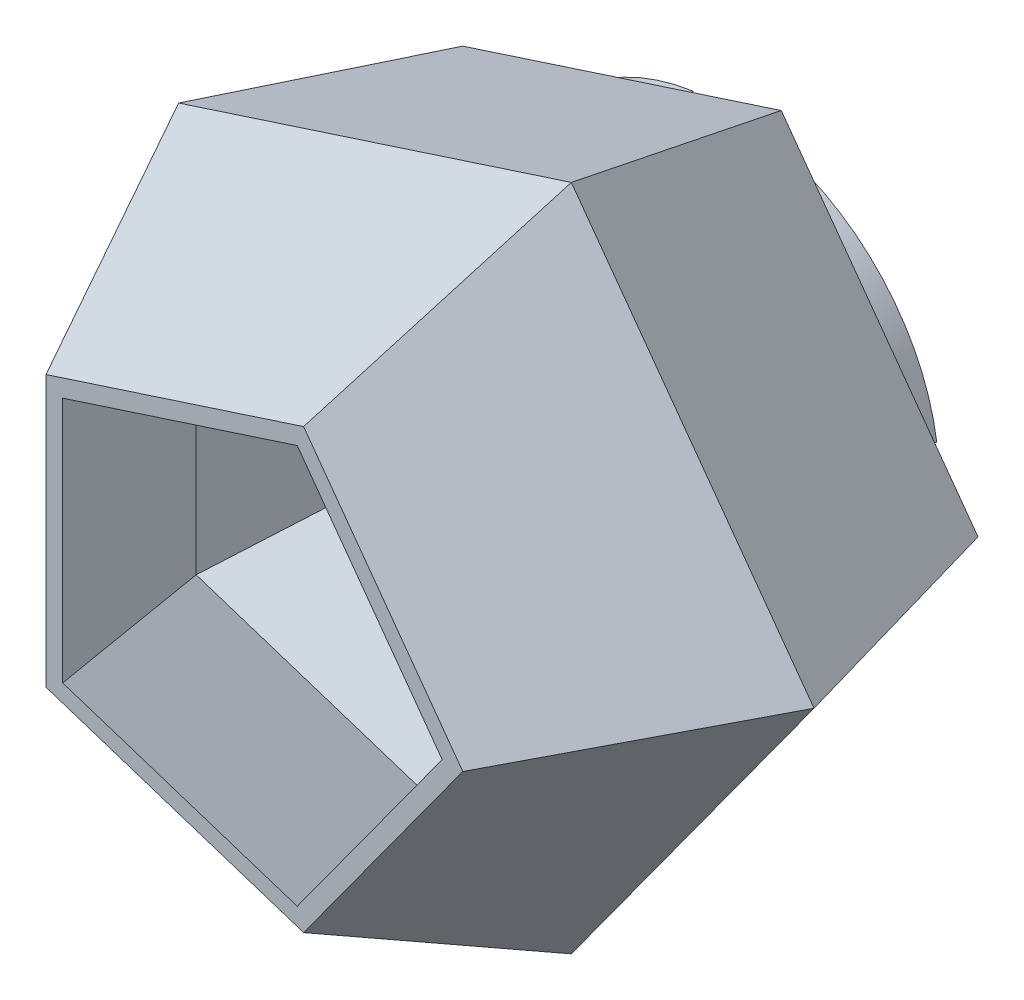
SolidWorks part; units mm, degrees
ref_plane "Alzado" through (0, 0, 0) normal (0, 0, 1) x (1, 0, 0)
ref_plane "Planta" through (0, 0, 0) normal (0, 1, 0) x (1, 0, 0)
ref_plane "Vista lateral" through (0, 0, 0) normal (1, 0, 0) x (0, 0, -1)
sketch "Croquis2" plane through (0, 0, 0) normal (0, 0, 1) x (1, 0, 0)
  line L1 (18.541, 0) -> (5.7295, 17.6336)
  line L2 (5.7295, 17.6336) -> (-15, 10.8981)
  line L3 (-15, 10.8981) -> (-15, -10.8981)
  line L4 (-15, -10.8981) -> (5.7295, -17.6336)
  line L5 (5.7295, -17.6336) -> (18.541, 0)
  circle A0 centre (0, 0) radius 15 construction
  dimension "D1" = 30
ref_plane "Plano1" through (0, 0, 15) normal (0, 0, 1) x (1, 0, 0)
sketch "Croquis3" plane through (0, 0, 15) normal (0, 0, 1) x (1, 0, 0)
  line L1 (22.8673, 0) -> (7.0664, 21.7481)
  line L2 (7.0664, 21.7481) -> (-18.5, 13.441)
  line L3 (-18.5, 13.441) -> (-18.5, -13.441)
  line L4 (-18.5, -13.441) -> (7.0664, -21.7481)
  line L5 (7.0664, -21.7481) -> (22.8673, 0)
  circle A0 centre (0, 0) radius 18.5 construction
  point P1 (7.1512, 21.7575)
  point P9 (22.7754, 0)
  point P10 (22.7754, 0)
  point P11 (22.8673, 0)
  dimension "D1" = 37
ref_plane "Plano2" through (0, 0, 30) normal (0, 0, 1) x (1, 0, 0)
sketch "Croquis4" plane through (0, 0, 30) normal (0, 0, 1) x (1, 0, 0)
  line L1 (15, 0) -> (4.6353, 14.2658)
  line L2 (4.6353, 14.2658) -> (-12.1353, 8.8168)
  line L3 (-12.1353, 8.8168) -> (-12.1353, -8.8168)
  line L4 (-12.1353, -8.8168) -> (4.6353, -14.2658)
  line L5 (4.6353, -14.2658) -> (15, 0)
  circle A0 centre (0, 0) radius 12.1353 construction
loft "Recubrir1" add profiles "Croquis2", "Croquis3"
loft "Recubrir2" add profiles "Croquis4" section face at (0, 0, 15) section "Croquis4"
sketch "Croquis5" plane through (0, 0, 30) normal (0, 0, 1) x (1, 0, 0)
  line L1 (12.6048, 0) -> (3.8951, 11.9879)
  line L2 (3.8951, 11.9879) -> (-10.1975, 7.4089)
  line L3 (-10.1975, 7.4089) -> (-10.1975, -7.4089)
  line L4 (-10.1975, -7.4089) -> (3.8951, -11.9879)
  line L5 (3.8951, -11.9879) -> (12.6048, 0)
  circle A0 centre (0, 0) radius 10.1975 construction
shell "Vaciado1" thickness 1
sketch "Croquis6" plane through (0, 0, 0) normal (0, 0, -1) x (-1, 0, 0)
  circle A0 centre (0, 0) radius 2.4804
extrude "Cortar-Extruir1" cut sketch "Croquis6" against normal blind 10
sketch "Croquis7" plane through (0, 0, 0) normal (0, 0, -1) x (-1, 0, 0)
  line L0 (-2, 13.8564) -> (-2, 11.3248)
  line L1 (2, 13.8564) -> (2, 11.3248)
  line L2 (0, 14) -> (0, -14) construction
  line L3 (-14, 0) -> (14, 0) construction
  line L4 (-13.8564, 2) -> (-11.3248, 2)
  line L5 (-13.8564, -2) -> (-11.3248, -2)
  line L6 (11.3248, 2) -> (13.8564, 2)
  line L8 (-2, -11.3248) -> (-2, -13.8564)
  line L9 (11.3248, -2) -> (13.8564, -2)
  line L10 (2, -11.3248) -> (2, -13.8564)
  arc A0 (-11.3248, -2) -> (-2, -11.3248) centre (0, 0) ccw
  arc A1 (-13.8564, -2) -> (-2, -13.8564) centre (0, 0) ccw
  arc A2 (11.3248, 2) -> (2, 11.3248) centre (0, 0) ccw
  arc A3 (13.8564, 2) -> (2, 13.8564) centre (0, 0) ccw
  arc A4 (2, -11.3248) -> (11.3248, -2) centre (0, 0) ccw
  arc A5 (2, -13.8564) -> (13.8564, -2) centre (0, 0) ccw
  arc A6 (-2, 13.8564) -> (-13.8564, 2) centre (0, 0) ccw
  arc A7 (-2, 11.3248) -> (-11.3248, 2) centre (0, 0) ccw
  dimension "D1" = 23
  dimension "D2" = 28
  dimension "D3" = 2
  dimension "D4" = 2
  dimension "D5" = 2
extrude "Saliente-Extruir1" add sketch "Croquis7" along normal blind 2
